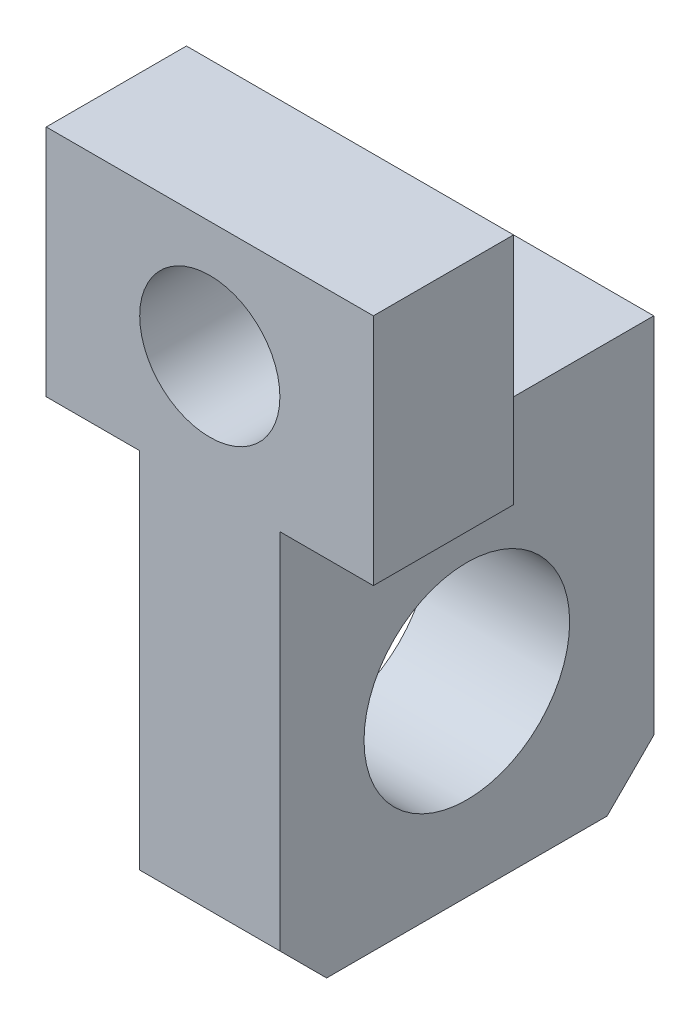
SolidWorks part; units mm, degrees
ref_plane "Front Plane" through (0, 0, 0) normal (1, 0, 0) x (0, 1, 0)
ref_plane "Top Plane" through (0, 0, 0) normal (0, 0, 1) x (0, 1, 0)
ref_plane "Right Plane" through (0, 0, 0) normal (0, 1, 0) x (-1, 0, 0)
sketch "Sketch7" plane through (0, 0, 0) normal (0, 0, 1) x (0, 1, 0)
  line L0 (11.1387, 0) -> (11.1387, -2.54)
  line L1 (0, 0) -> (11.1387, 0)
  line L2 (0, 0) -> (0, 3.81)
  line L3 (0, 3.81) -> (11.1387, 3.81)
  line L5 (11.1387, -2.54) -> (17.4887, -2.54)
  line L6 (17.4887, -2.54) -> (17.4887, 6.35)
  line L7 (17.4887, 6.35) -> (11.1387, 6.35)
  line L8 (11.1387, 6.35) -> (11.1387, 3.81)
  line L9 (0, 1.905) -> (17.4887, 1.905) construction
  circle A0 centre (14.3137, 1.905) radius 1.905
  dimension "D4" = 3.81
  dimension "D1" = 3.81
  dimension "D2" = 2.54
  dimension "D3" = 6.35
  dimension "D5" = 3.175
extrude "base" add sketch "Sketch7" along normal blind 10.16
sketch "Sketch8" plane through (0, 0, 0) normal (1, 0, 0) x (0, 1, 0)
  line L0 (0, 5.08) -> (5.08, 5.08) construction
  line L1 (0, 10.16) -> (0, 0) construction
  circle A0 centre (5.08, 5.08) radius 2.794
  dimension "D1" = 5.588
  dimension "D2" = 5.08
extrude "lever_hole" cut sketch "Sketch8" against normal up to next
chamfer "Chamfer2" distance 1.27 angle 45 2 edges at (-1.905, 0, 10.16) (-1.905, 0, 0)
sketch "Sketch9" plane through (0, 0, 0) normal (0, 0, -1) x (1, 0, 0)
  line L1 (-6.35, -11.1387) -> (2.54, -11.1387)
  line L2 (-6.35, -11.1387) -> (-6.35, -17.4887)
  line L3 (-6.35, -17.4887) -> (2.54, -17.4887)
  line L4 (2.54, -11.1387) -> (2.54, -17.4887)
extrude "Cut-Extrude4" cut sketch "Sketch9" against normal blind 6.35
